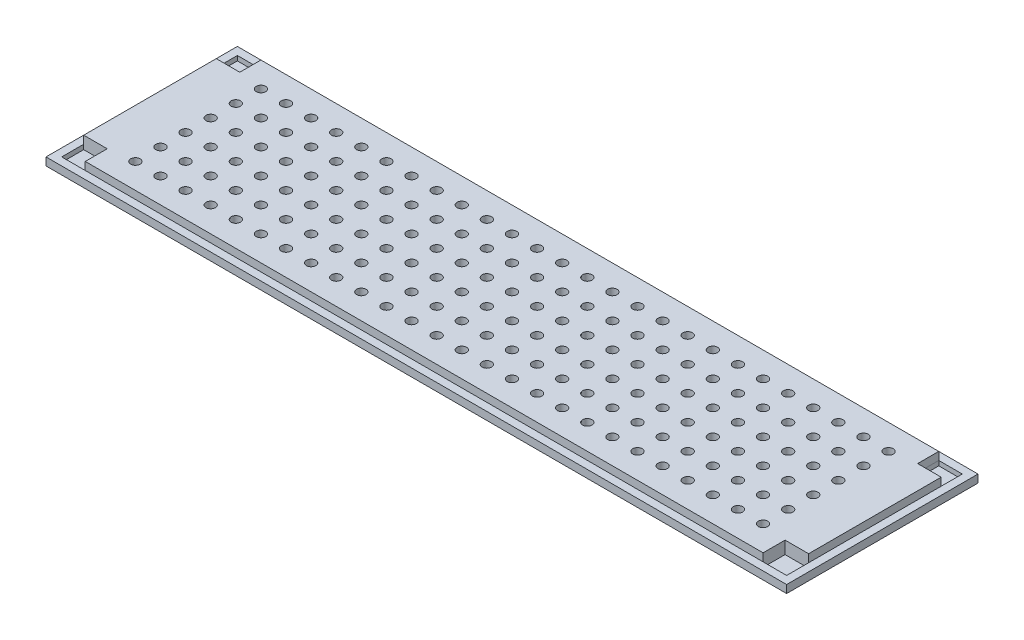
SolidWorks part; units mm, degrees
ref_plane "Front Plane" through (0, 0, 0) normal (0, 0, 1) x (1, 0, 0)
ref_plane "Top Plane" through (0, 0, 0) normal (0, 1, 0) x (1, 0, 0)
ref_plane "Right Plane" through (0, 0, 0) normal (1, 0, 0) x (0, 0, -1)
sketch "Sketch1" plane through (0, 0, 0) normal (0, 1, 0) x (1, 0, 0)
  line L5 (-118, 30.49) -> (118, 30.49)
  line L6 (-118, 30.49) -> (-118, -30.49)
  line L7 (-118, -30.49) -> (118, -30.49)
  line L8 (118, 30.49) -> (118, -30.49)
  line L9 (-118, 30.49) -> (118, -30.49) construction
  line L10 (-118, -30.49) -> (118, 30.49) construction
  point P0 (0, 0)
  point P1 (0, 0)
  dimension "D1" = 236
  dimension "D2" = 60.98
extrude "Boss-Extrude2" add sketch "Sketch1" along normal blind 2.5
sketch "Sketch2" plane through (0, 2.5, 0) normal (0, 1, 0) x (1, 0, 0)
  line L0 (-107.9977, 27.99) -> (-107.9977, 21.2567)
  line L7 (-107.9977, 21.2567) -> (-115.5, 21.2567)
  line L8 (-115.5, -20.9859) -> (-115.5, 21.2567) construction
  line L9 (-115.5, 21.2567) -> (-115.5, -20.9859)
  line L10 (-115.5, -20.9859) -> (-107.9977, -20.9859)
  line L11 (-107.9977, -20.9859) -> (-107.9977, -27.9859)
  line L12 (-107.9977, -27.9859) -> (107.9977, -27.9859)
  line L13 (107.9977, -27.9859) -> (107.9977, -20.9859)
  line L14 (107.9977, -20.9859) -> (115.5, -20.9859)
  line L15 (115.5, -20.9859) -> (115.5, 21.2567)
  line L16 (115.5, 21.2567) -> (108, 21.2581)
  line L17 (108, 21.2581) -> (107.9977, 27.99)
  line L18 (107.9977, 27.99) -> (-107.9977, 27.99)
  point P0 (0, 0)
  point P31 (-108.0342, 33.4739)
  dimension "D1" = 215.9954
extrude "Boss-Extrude3" add sketch "Sketch2" along normal blind 2.5
sketch "Sketch4" plane through (0, 2.5, 0) normal (0, 1, 0) x (1, 0, 0)
  line L0 (-107.9977, 27.99) -> (-115.5, 27.99)
  line L1 (-115.5, 21.2567) -> (-115.5, 27.99)
  line L2 (-107.9977, 21.2567) -> (-115.5, 21.2567) construction
  line L3 (-115.5, 21.2567) -> (-115.5, -20.9859) construction
  line L4 (-115.5, 21.2567) -> (-107.9977, 21.2567)
  line L5 (-107.9977, 21.2567) -> (-107.9977, 27.99)
  line L6 (0, -2.75) -> (0, 2.75) construction
  line L9 (-107.9977, -21.2567) -> (-107.9977, -27.99)
  line L10 (-107.9977, -27.99) -> (-115.5, -27.99)
  line L11 (-115.5, -21.2567) -> (-115.5, -27.99)
  line L12 (-115.5, -21.2567) -> (-115.5, -20.9859)
  line L13 (-115.5, -20.9859) -> (-107.9977, -20.9859)
  line L14 (-115.5, -20.9859) -> (-107.9977, -20.9859) construction
  line L15 (-115.5, -20.9859) -> (-107.9977, -20.9859) construction
  line L16 (-107.9977, -20.9859) -> (-107.9977, -21.2567)
  line L17 (115.5, -21.2567) -> (115.5, -20.9859)
  line L18 (115.5, -20.9859) -> (107.9977, -20.9859)
  line L19 (107.9977, -20.9859) -> (107.9977, -21.2567)
  line L20 (107.9977, -21.2567) -> (107.9977, -27.99)
  line L21 (107.9977, -27.99) -> (115.5, -27.99)
  line L22 (115.5, -21.2567) -> (115.5, -27.99)
  line L23 (115.5, 21.2567) -> (107.9977, 21.2567)
  line L24 (107.9977, 21.2567) -> (107.9977, 27.99)
  line L25 (107.9977, 27.99) -> (115.5, 27.99)
  line L26 (115.5, 21.2567) -> (115.5, 27.99)
extrude "Cut-Extrude2" cut sketch "Sketch4" against normal blind 1.5
sketch "Sketch5" plane through (0, 5, 0) normal (0, 1, 0) x (1, 0, 0)
  line L0 (107.9977, 27.99) -> (-107.9977, 27.99) construction
  line L1 (-107.9977, 21.2567) -> (-107.9977, 27.99) construction
  circle A0 centre (-99.9977, 19.99) radius 1.5
  circle A1 centre (-91.9977, 19.99) radius 1.5
  circle A2 centre (-83.9977, 19.99) radius 1.5
  circle A3 centre (-75.9977, 19.99) radius 1.5
  circle A4 centre (-67.9977, 19.99) radius 1.5
  circle A5 centre (-59.9977, 19.99) radius 1.5
  circle A6 centre (-51.9977, 19.99) radius 1.5
  circle A7 centre (-43.9977, 19.99) radius 1.5
  circle A8 centre (-35.9977, 19.99) radius 1.5
  circle A9 centre (-27.9977, 19.99) radius 1.5
  circle A10 centre (-19.9977, 19.99) radius 1.5
  circle A11 centre (-11.9977, 19.99) radius 1.5
  circle A12 centre (-3.9977, 19.99) radius 1.5
  circle A13 centre (4.0023, 19.99) radius 1.5
  circle A14 centre (12.0023, 19.99) radius 1.5
  circle A15 centre (20.0023, 19.99) radius 1.5
  circle A16 centre (28.0023, 19.99) radius 1.5
  circle A17 centre (36.0023, 19.99) radius 1.5
  circle A18 centre (44.0023, 19.99) radius 1.5
  circle A19 centre (52.0023, 19.99) radius 1.5
  circle A20 centre (60.0023, 19.99) radius 1.5
  circle A21 centre (68.0023, 19.99) radius 1.5
  circle A22 centre (76.0023, 19.99) radius 1.5
  circle A23 centre (84.0023, 19.99) radius 1.5
  circle A24 centre (92.0023, 19.99) radius 1.5
  circle A25 centre (100.0023, 19.99) radius 1.5
  circle A26 centre (-91.9977, 11.99) radius 1.5
  circle A27 centre (-83.9977, 11.99) radius 1.5
  circle A28 centre (-75.9977, 11.99) radius 1.5
  circle A29 centre (-67.9977, 11.99) radius 1.5
  circle A30 centre (-59.9977, 11.99) radius 1.5
  circle A31 centre (-51.9977, 11.99) radius 1.5
  circle A32 centre (-43.9977, 11.99) radius 1.5
  circle A33 centre (-35.9977, 11.99) radius 1.5
  circle A34 centre (-27.9977, 11.99) radius 1.5
  circle A35 centre (-19.9977, 11.99) radius 1.5
  circle A36 centre (-11.9977, 11.99) radius 1.5
  circle A37 centre (-3.9977, 11.99) radius 1.5
  circle A38 centre (4.0023, 11.99) radius 1.5
  circle A39 centre (12.0023, 11.99) radius 1.5
  circle A40 centre (20.0023, 11.99) radius 1.5
  circle A41 centre (28.0023, 11.99) radius 1.5
  circle A42 centre (36.0023, 11.99) radius 1.5
  circle A43 centre (44.0023, 11.99) radius 1.5
  circle A44 centre (52.0023, 11.99) radius 1.5
  circle A45 centre (60.0023, 11.99) radius 1.5
  circle A46 centre (68.0023, 11.99) radius 1.5
  circle A47 centre (76.0023, 11.99) radius 1.5
  circle A48 centre (84.0023, 11.99) radius 1.5
  circle A49 centre (92.0023, 11.99) radius 1.5
  circle A50 centre (100.0023, 11.99) radius 1.5
  circle A51 centre (-91.9977, 3.99) radius 1.5
  circle A52 centre (-83.9977, 3.99) radius 1.5
  circle A53 centre (-75.9977, 3.99) radius 1.5
  circle A54 centre (-67.9977, 3.99) radius 1.5
  circle A55 centre (-59.9977, 3.99) radius 1.5
  circle A56 centre (-51.9977, 3.99) radius 1.5
  circle A57 centre (-43.9977, 3.99) radius 1.5
  circle A58 centre (-35.9977, 3.99) radius 1.5
  circle A59 centre (-27.9977, 3.99) radius 1.5
  circle A60 centre (-19.9977, 3.99) radius 1.5
  circle A61 centre (-11.9977, 3.99) radius 1.5
  circle A62 centre (-3.9977, 3.99) radius 1.5
  circle A63 centre (4.0023, 3.99) radius 1.5
  circle A64 centre (12.0023, 3.99) radius 1.5
  circle A65 centre (20.0023, 3.99) radius 1.5
  circle A66 centre (28.0023, 3.99) radius 1.5
  circle A67 centre (36.0023, 3.99) radius 1.5
  circle A68 centre (44.0023, 3.99) radius 1.5
  circle A69 centre (52.0023, 3.99) radius 1.5
  circle A70 centre (60.0023, 3.99) radius 1.5
  circle A71 centre (68.0023, 3.99) radius 1.5
  circle A72 centre (76.0023, 3.99) radius 1.5
  circle A73 centre (84.0023, 3.99) radius 1.5
  circle A74 centre (92.0023, 3.99) radius 1.5
  circle A75 centre (100.0023, 3.99) radius 1.5
  circle A76 centre (-91.9977, -4.01) radius 1.5
  circle A77 centre (-83.9977, -4.01) radius 1.5
  circle A78 centre (-75.9977, -4.01) radius 1.5
  circle A79 centre (-67.9977, -4.01) radius 1.5
  circle A80 centre (-59.9977, -4.01) radius 1.5
  circle A81 centre (-51.9977, -4.01) radius 1.5
  circle A82 centre (-43.9977, -4.01) radius 1.5
  circle A83 centre (-35.9977, -4.01) radius 1.5
  circle A84 centre (-27.9977, -4.01) radius 1.5
  circle A85 centre (-19.9977, -4.01) radius 1.5
  circle A86 centre (-11.9977, -4.01) radius 1.5
  circle A87 centre (-3.9977, -4.01) radius 1.5
  circle A88 centre (4.0023, -4.01) radius 1.5
  circle A89 centre (12.0023, -4.01) radius 1.5
  circle A90 centre (20.0023, -4.01) radius 1.5
  circle A91 centre (28.0023, -4.01) radius 1.5
  circle A92 centre (36.0023, -4.01) radius 1.5
  circle A93 centre (44.0023, -4.01) radius 1.5
  circle A94 centre (52.0023, -4.01) radius 1.5
  circle A95 centre (60.0023, -4.01) radius 1.5
  circle A96 centre (68.0023, -4.01) radius 1.5
  circle A97 centre (76.0023, -4.01) radius 1.5
  circle A98 centre (84.0023, -4.01) radius 1.5
  circle A99 centre (92.0023, -4.01) radius 1.5
  circle A100 centre (100.0023, -4.01) radius 1.5
  circle A101 centre (-91.9977, -12.01) radius 1.5
  circle A102 centre (-83.9977, -12.01) radius 1.5
  circle A103 centre (-75.9977, -12.01) radius 1.5
  circle A104 centre (-67.9977, -12.01) radius 1.5
  circle A105 centre (-59.9977, -12.01) radius 1.5
  circle A106 centre (-51.9977, -12.01) radius 1.5
  circle A107 centre (-43.9977, -12.01) radius 1.5
  circle A108 centre (-35.9977, -12.01) radius 1.5
  circle A109 centre (-27.9977, -12.01) radius 1.5
  circle A110 centre (-19.9977, -12.01) radius 1.5
  circle A111 centre (-11.9977, -12.01) radius 1.5
  circle A112 centre (-3.9977, -12.01) radius 1.5
  circle A113 centre (4.0023, -12.01) radius 1.5
  circle A114 centre (12.0023, -12.01) radius 1.5
  circle A115 centre (20.0023, -12.01) radius 1.5
  circle A116 centre (28.0023, -12.01) radius 1.5
  circle A117 centre (36.0023, -12.01) radius 1.5
  circle A118 centre (44.0023, -12.01) radius 1.5
  circle A119 centre (52.0023, -12.01) radius 1.5
  circle A120 centre (60.0023, -12.01) radius 1.5
  circle A121 centre (68.0023, -12.01) radius 1.5
  circle A122 centre (76.0023, -12.01) radius 1.5
  circle A123 centre (84.0023, -12.01) radius 1.5
  circle A124 centre (92.0023, -12.01) radius 1.5
  circle A125 centre (100.0023, -12.01) radius 1.5
  circle A126 centre (-91.9977, -20.01) radius 1.5
  circle A127 centre (-83.9977, -20.01) radius 1.5
  circle A128 centre (-75.9977, -20.01) radius 1.5
  circle A129 centre (-67.9977, -20.01) radius 1.5
  circle A130 centre (-59.9977, -20.01) radius 1.5
  circle A131 centre (-51.9977, -20.01) radius 1.5
  circle A132 centre (-43.9977, -20.01) radius 1.5
  circle A133 centre (-35.9977, -20.01) radius 1.5
  circle A134 centre (-27.9977, -20.01) radius 1.5
  circle A135 centre (-19.9977, -20.01) radius 1.5
  circle A136 centre (-11.9977, -20.01) radius 1.5
  circle A137 centre (-3.9977, -20.01) radius 1.5
  circle A138 centre (4.0023, -20.01) radius 1.5
  circle A139 centre (12.0023, -20.01) radius 1.5
  circle A140 centre (20.0023, -20.01) radius 1.5
  circle A141 centre (28.0023, -20.01) radius 1.5
  circle A142 centre (36.0023, -20.01) radius 1.5
  circle A143 centre (44.0023, -20.01) radius 1.5
  circle A144 centre (52.0023, -20.01) radius 1.5
  circle A145 centre (60.0023, -20.01) radius 1.5
  circle A146 centre (68.0023, -20.01) radius 1.5
  circle A147 centre (76.0023, -20.01) radius 1.5
  circle A148 centre (84.0023, -20.01) radius 1.5
  circle A149 centre (92.0023, -20.01) radius 1.5
  circle A150 centre (100.0023, -20.01) radius 1.5
  circle A151 centre (-99.9977, 11.99) radius 1.5
  circle A152 centre (-99.9977, 3.99) radius 1.5
  circle A153 centre (-99.9977, -4.01) radius 1.5
  circle A154 centre (-99.9977, -12.01) radius 1.5
  circle A155 centre (-99.9977, -20.01) radius 1.5
  dimension "D1" = 3
  dimension "D2" = 8
  dimension "D3" = 8
  dimension "D4" = 26
  dimension "D5" = 6
extrude "Cut-Extrude3" cut sketch "Sketch5" against normal blind 10
